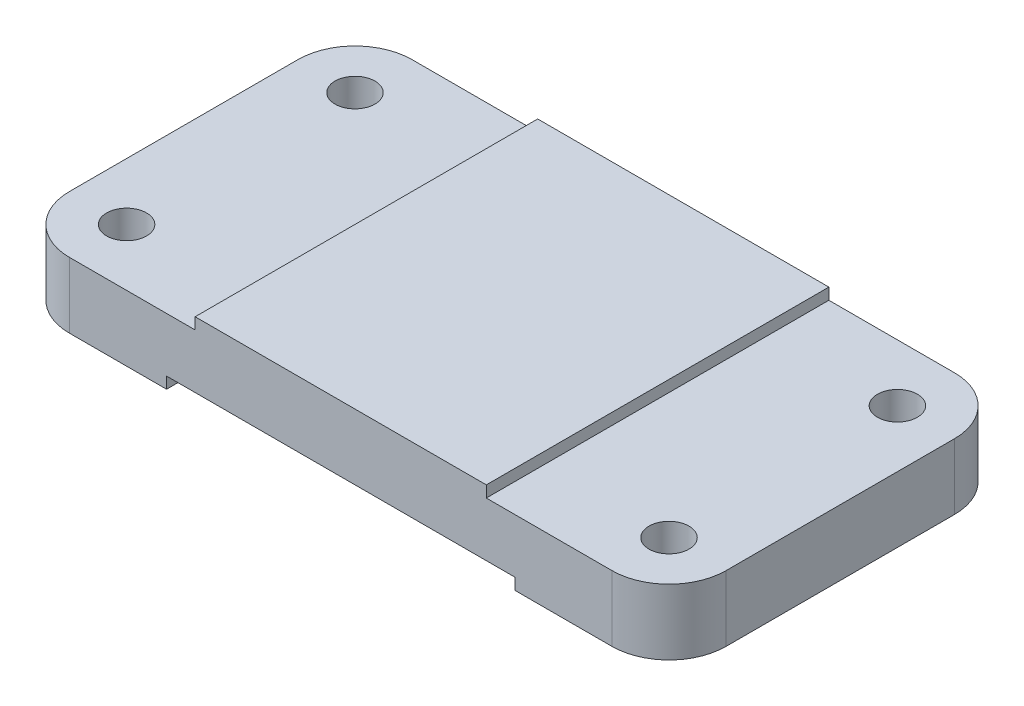
SolidWorks part; units mm, degrees
ref_plane "Front Plane" through (0, 0, 0) normal (0, 0, 1) x (1, 0, 0)
ref_plane "Top Plane" through (0, 0, 0) normal (0, 1, 0) x (1, 0, 0)
ref_plane "Right Plane" through (0, 0, 0) normal (1, 0, 0) x (0, 0, -1)
sketch "Sketch1" plane through (0, 0, 0) normal (0, 1, 0) x (1, 0, 0)
  line L1 (-95, 60) -> (95, 60)
  line L2 (-115, 40) -> (-115, -40)
  line L3 (-95, -60) -> (95, -60)
  line L4 (115, 40) -> (115, -40)
  line L5 (-115, 60) -> (115, -60) construction
  line L6 (-115, -60) -> (115, 60) construction
  arc A0 (95, 60) -> (115, 40) centre (95, 40) cw
  arc A1 (115, -40) -> (95, -60) centre (95, -40) cw
  arc A2 (-115, -40) -> (-95, -60) centre (-95, -40) ccw
  arc A3 (-95, 60) -> (-115, 40) centre (-95, 40) ccw
  point P0 (0, 0)
  dimension "D1" = 20
  dimension "D2" = 230
  dimension "D3" = 120
extrude "Boss-Extrude1" add sketch "Sketch1" along normal blind 23
sketch "Sketch3" plane through (0, 23, 0) normal (0, 1, 0) x (1, 0, 0)
  line L0 (-95, -60) -> (95, -60) construction
  line L1 (-51, 60) -> (51, 60)
  line L2 (-51, 60) -> (-51, -60)
  line L3 (-51, -60) -> (51, -60)
  line L4 (51, 60) -> (51, -60)
  line L5 (-51, 60) -> (51, -60) construction
  line L6 (-51, -60) -> (51, 60) construction
  point P0 (0, 0)
  dimension "D1" = 102
extrude "Boss-Extrude2" add sketch "Sketch3" along normal blind 4
sketch "Sketch4" plane through (0, 0, 0) normal (0, -1, 0) x (1, 0, 0)
  line L0 (95, -60) -> (-95, -60) construction
  line L1 (-61, 60) -> (61, 60)
  line L2 (-61, 60) -> (-61, -60)
  line L3 (-61, -60) -> (61, -60)
  line L4 (61, 60) -> (61, -60)
  line L5 (-61, 60) -> (61, -60) construction
  line L6 (-61, -60) -> (61, 60) construction
  point P0 (0, 0)
  dimension "D1" = 122
extrude "Cut-Extrude1" cut sketch "Sketch4" against normal blind 4
sketch "Sketch5" plane through (0, 23, 0) normal (0, 1, 0) x (1, 0, 0)
  circle A0 centre (-95, 40) radius 8
  dimension "D1" = 16
hole_wizard "M16 Tapped Hole1" positions "3DSketch4" profile "Sketch8" tap size "M16" standard "ISO" end condition through all
sketch3d "3DSketch4"
  line L0 (-95, 23, 40) -> (-95, 0, 40) construction
  line L1 (95, 23, -40) -> (95, 0, -40) construction
  line L2 (95, 23, 40) -> (95, 0, 40) construction
  point P0 (-95, 23, -40)
  point P3 (-95, 23, 40)
  point P7 (95, 23, -40)
  point P11 (95, 23, 40)
sketch "Sketch8" plane through (-95, 23, -40) normal (1, 0, 0) x (0, 0, 1)
  line L0 (0, 0) -> (0, 23)
  line L1 (0, 23) -> (7, 23)
  line L2 (7, 23) -> (7, 0)
  line L5 (7, 0) -> (0, 0)
  line L11 (0, -6.35) -> (0, 107.95) construction
  dimension "Thru Tap Drill Dia." = 14
  dimension "Thru Tap Drill Depth" = 23
cosmetic thread "Hole Thread1" parameters "D2"=16
cosmetic thread "Hole Thread2" parameters "D2"=16
cosmetic thread "Hole Thread3" parameters "D2"=16
cosmetic thread "Hole Thread4" parameters "D2"=16
